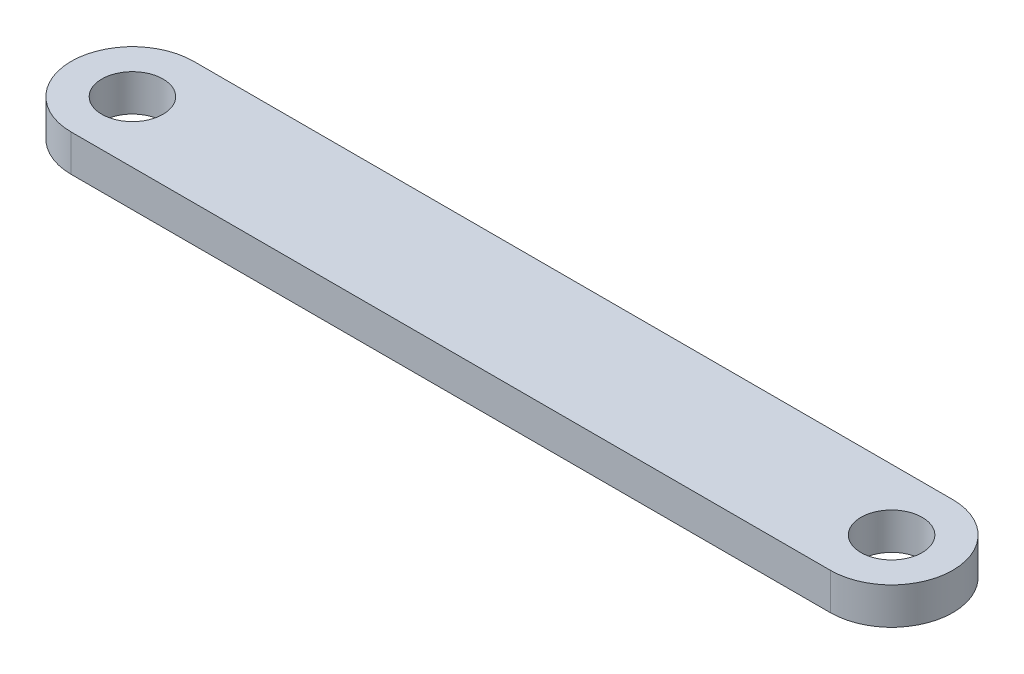
SolidWorks part; units mm, degrees
ref_plane "Front Plane" through (0, 0, 0) normal (0, 0, 1) x (1, 0, 0)
ref_plane "Top Plane" through (0, 0, 0) normal (0, 1, 0) x (1, 0, 0)
ref_plane "Right Plane" through (0, 0, 0) normal (1, 0, 0) x (0, 0, -1)
sketch "Sketch1" plane through (0, 0, 0) normal (0, 1, 0) x (1, 0, 0)
  line L0 (-39.37, 0) -> (39.37, 0) construction
  line L1 (-39.37, 6.35) -> (39.37, 6.35)
  line L2 (-39.37, -6.35) -> (39.37, -6.35)
  arc A0 (-39.37, 6.35) -> (-39.37, -6.35) centre (-39.37, 0) ccw
  arc A1 (39.37, -6.35) -> (39.37, 6.35) centre (39.37, 0) ccw
  circle A2 centre (-39.37, 0) radius 3.175
  circle A3 centre (39.37, 0) radius 3.175
  point P3 (0, 0)
  dimension "D2" = 6.35
  dimension "D3" = 6.35
  dimension "D4" = 6.35
  dimension "D1" = 78.74
extrude "Boss-Extrude1" add sketch "Sketch1" along normal blind 3.81
